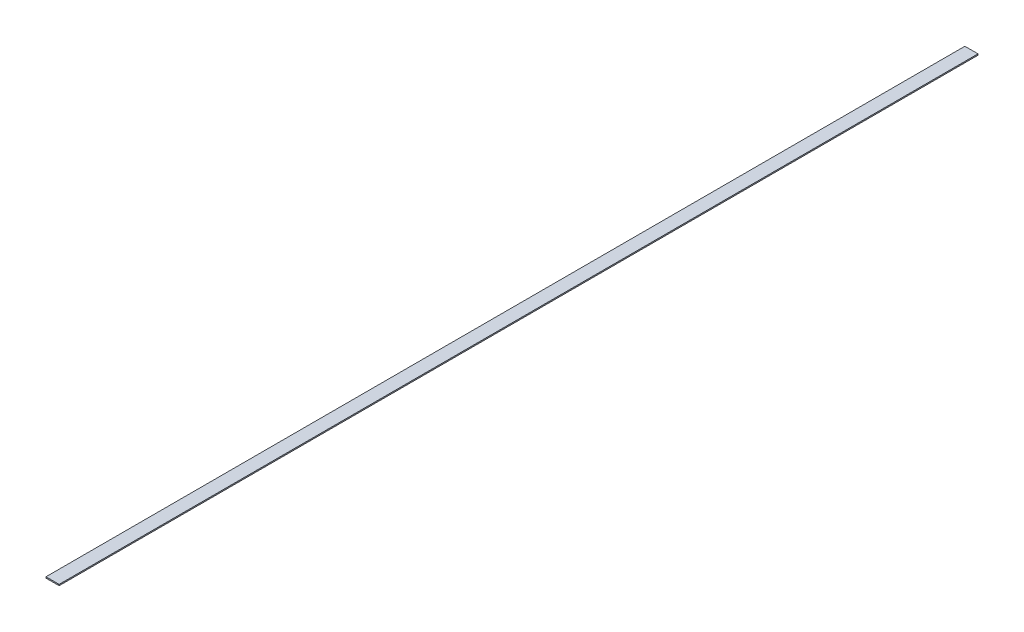
SolidWorks part; units mm, degrees
ref_plane "Front Plane" through (0, 0, 0) normal (0, 0, 1) x (1, 0, 0)
ref_plane "Top Plane" through (0, 0, 0) normal (0, 1, 0) x (1, 0, 0)
ref_plane "Right Plane" through (0, 0, 0) normal (1, 0, 0) x (0, 0, -1)
sketch "Sketch1" plane through (0, 0, 0) normal (0, 0, 1) x (1, 0, 0)
  line L1 (-44.4152, 29.4091) -> (6.3848, 29.4091)
  line L2 (-44.4152, 29.4091) -> (-44.4152, 24.6466)
  line L3 (-44.4152, 24.6466) -> (6.3848, 24.6466)
  line L4 (6.3848, 29.4091) -> (6.3848, 24.6466)
  dimension "D1" = 50.8
  dimension "D2" = 4.7625
extrude "Boss-Extrude1" add sketch "Sketch1" along normal blind 3556
